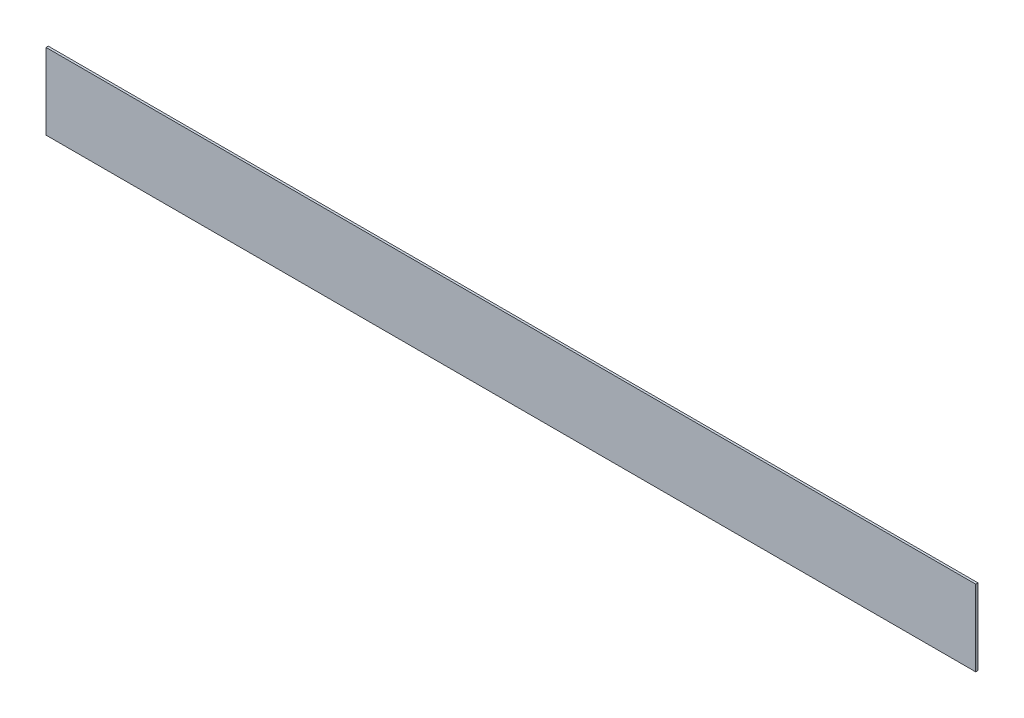
SolidWorks part; units mm, degrees
ref_plane "前视基准面" through (0, 0, 0) normal (0, 0, 1) x (1, 0, 0)
ref_plane "上视基准面" through (0, 0, 0) normal (0, 1, 0) x (1, 0, 0)
ref_plane "右视基准面" through (0, 0, 0) normal (1, 0, 0) x (0, 0, -1)
other "Configuration Table"
sketch "草图1" plane through (0, 0, 0) normal (0, 0, 1) x (1, 0, 0)
  line L1 (0, 0) -> (2056, 0)
  line L2 (0, 0) -> (0, 168)
  line L3 (0, 168) -> (2056, 168)
  line L4 (2056, 0) -> (2056, 168)
  dimension "D1" = 168
  dimension "D2" = 2056
extrude "凸台-拉伸1" add sketch "草图1" along normal blind 5
